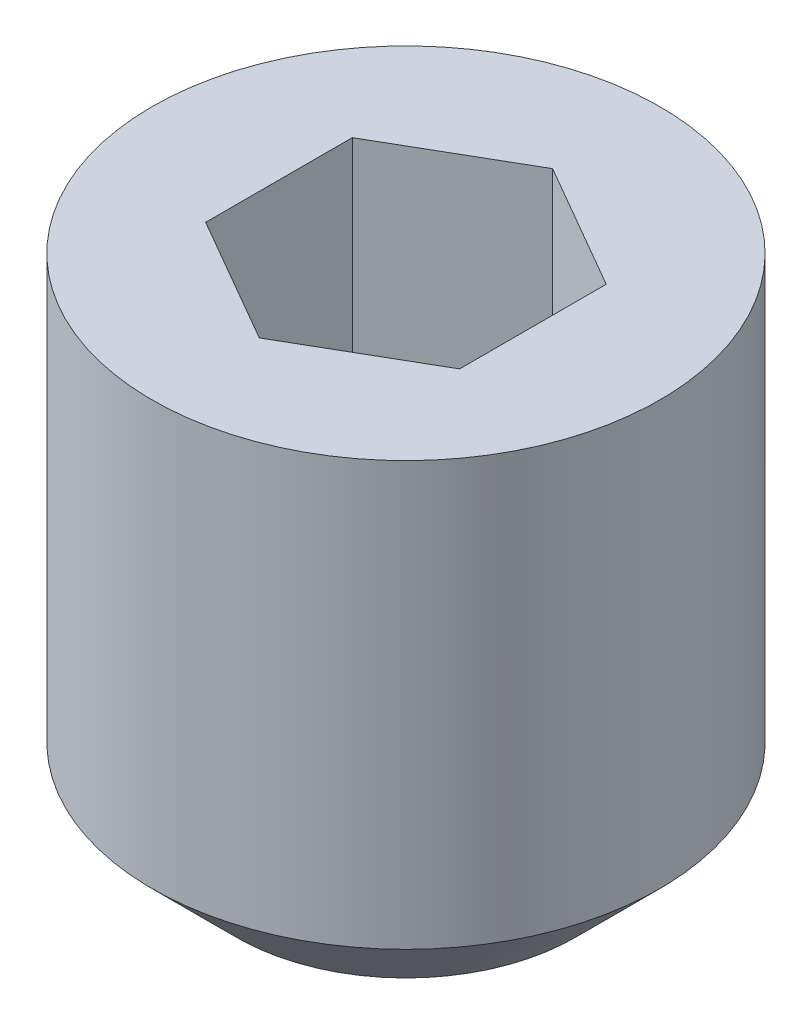
SolidWorks part; units mm, degrees
ref_plane "Front Plane" through (0, 0, 0) normal (0, 0, 1) x (1, 0, 0)
ref_plane "Top Plane" through (0, 0, 0) normal (0, 1, 0) x (1, 0, 0)
ref_plane "Right Plane" through (0, 0, 0) normal (1, 0, 0) x (0, 0, -1)
sketch "Sketch1" plane through (0, 0, 0) normal (0, 0, 1) x (1, 0, 0)
  line L0 (0, 3) -> (0, 0) construction
  line L1 (0, 3) -> (1.5, 3)
  line L2 (1.5, 3) -> (1.5, 0)
  line L3 (1.5, 0) -> (0, 0)
  line L4 (0, 3) -> (0, 0)
  dimension "TPC" = 3
  dimension "SS_L" = 3
revolve "Revolve1" add sketch "Sketch1" angle 360 about L0
cosmetic thread "Cosmetic Thread1" parameters "SS_D1_s"=2.439
sketch "Sketch2" plane through (0, 0, 0) normal (0, 0, 1) x (1, 0, 0)
  line L0 (0, 3) -> (0, 1.367) construction
  line L1 (0, 3) -> (0.75, 3)
  line L2 (0.75, 3) -> (0.75, 1.8)
  line L3 (0.75, 1.8) -> (0, 1.367)
  line L4 (0, 3) -> (0, 1.367)
  line L5 (1.5, 3) -> (-1.5, 3) construction
  dimension "D3" = 60
  dimension "SS_C" = 1.2
  dimension "SS_B" = 1.5
revolve "Cut-Revolve1" cut sketch "Sketch2" angle 360 about L0
sketch "Sketch3" plane through (0, 3, 0) normal (0, 1, 0) x (1, 0, 0)
  line L1 (0, 0.866) -> (-0.75, 0.433)
  line L2 (-0.75, 0.433) -> (-0.75, -0.433)
  line L3 (-0.75, -0.433) -> (0, -0.866)
  line L4 (0, -0.866) -> (0.75, -0.433)
  line L5 (0.75, -0.433) -> (0.75, 0.433)
  line L6 (0.75, 0.433) -> (0, 0.866)
  circle A0 centre (0, 0) radius 0.75 construction
  circle A1 centre (0, 0) radius 0.75 construction
extrude "Cut-Extrude1" cut sketch "Sketch3" against normal blind 1.2
sketch "Sketch4" plane through (0, 0, 0) normal (0, 0, 1) x (1, 0, 0)
  line L0 (1, 0) -> (1.5, 0)
  line L1 (1.5, 0) -> (1.5, 0.5)
  line L2 (1.5, 0.5) -> (1, 0)
  line L4 (-1.5, 0) -> (1.5, 0) construction
  line L5 (0, 0) -> (0, 3) construction
  line L6 (1.5, 3) -> (-1.5, 3) construction
  line L7 (1.5, 3) -> (1.5, 0) construction
  dimension "D1" = 45
  dimension "SS_D_s" = 2
revolve "Cut-Revolve2" cut sketch "Sketch4" angle 360 about L5
